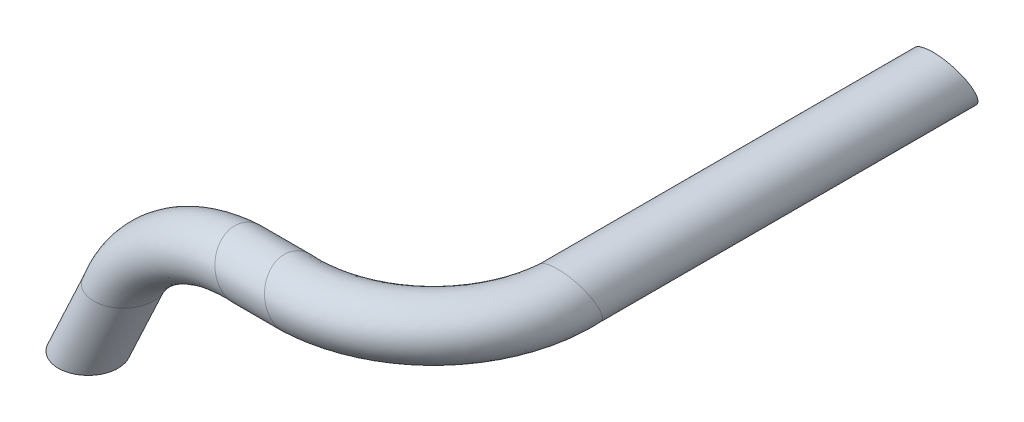
SolidWorks part; units mm, degrees
ref_plane "Front Plane" through (0, 0, 0) normal (0, 0, 1) x (1, 0, 0)
ref_plane "Top Plane" through (0, 0, 0) normal (0, 1, 0) x (1, 0, 0)
ref_plane "Right Plane" through (0, 0, 0) normal (1, 0, 0) x (0, 0, -1)
sketch3d "3DSketch1"
  line L0 (0, 0, 0) -> (2.0723, 4.444, 0)
  line L1 (9.3227, 9.0631, 0) -> (12.2262, 9.0631, 0)
  line L2 (20.2262, 9.0631, -8) -> (20.2262, 9.0631, -30)
  line L3 (0, 0, 0) -> (0, 40.6419, 0) construction
  arc A0 (12.2262, 9.0631, 0) -> (20.2262, 9.0631, -8) centre (12.2262, 9.0631, -8) ccw
  arc A1 (9.3227, 9.0631, 0) -> (2.0723, 4.444, 0) centre (9.3227, 1.0631, 0) ccw
  point P5 (0, 0, 0)
  point P9 (20.2262, 9.0631, 0)
  point P10 (12.2262, 17.0631, -8)
  point P13 (4.2262, 9.0631, 0)
  point P14 (9.3227, 1.0631, 8)
  dimension "D1" = 25
  dimension "D5" = 8
  dimension "D2" = 10
  dimension "D3" = 16
  dimension "D4" = 30
sketch "Sketch1" plane through (0, 0, 0) normal (0, 1, 0) x (1, 0, 0)
  circle A0 centre (0, 0) radius 1.75
  dimension "D1" = 3.5
sweep "Sweep1" add profiles "Sketch1" path "3DSketch1"
